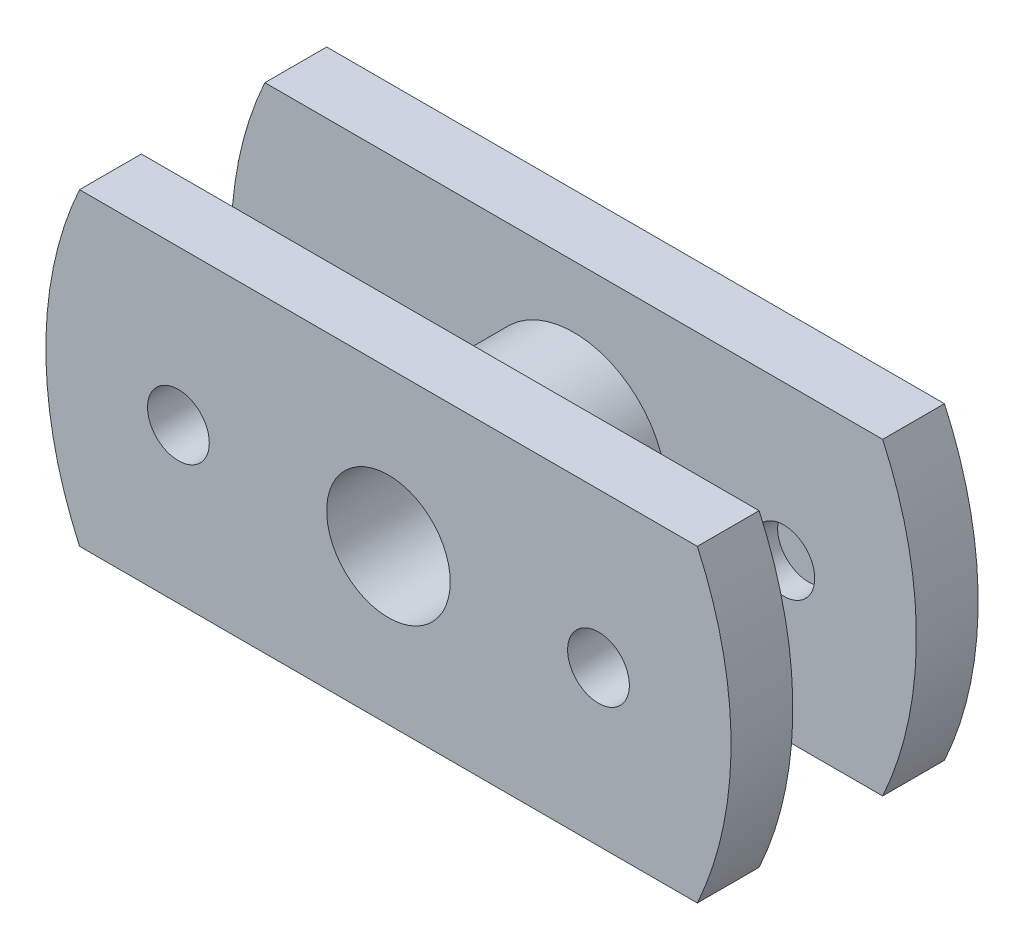
SolidWorks part; units mm, degrees
ref_plane "Front Plane" through (0, 0, 0) normal (0, 0, 1) x (1, 0, 0)
ref_plane "Top Plane" through (0, 0, 0) normal (0, 1, 0) x (1, 0, 0)
ref_plane "Right Plane" through (0, 0, 0) normal (1, 0, 0) x (0, 0, -1)
sketch "Sketch1" plane through (0, 0, 0) normal (0, 0, 1) x (1, 0, 0)
  line L0 (-25, 12.5) -> (-25, -12.5) construction
  line L1 (-25, -12.5) -> (25, -12.5)
  line L3 (-25, 12.5) -> (25, 12.5)
  line L5 (-25, -12.5) -> (25, 12.5) construction
  line L6 (-25, 12.5) -> (25, -12.5) construction
  line L7 (25, 12.5) -> (25, -12.5) construction
  arc A0 (-25, 12.5) -> (-25, -12.5) centre (2.2718, 0) ccw
  arc A1 (25, 12.5) -> (25, -12.5) centre (-2.2718, 0) cw
  point P0 (0, 0)
  dimension "D3" = 30
  dimension "D4" = 30
  dimension "D1" = 50
  dimension "D2" = 25
  dimension "D5" = 50
extrude "Boss-Extrude1" add sketch "Sketch1" along normal blind 5
sketch "Sketch2" plane through (0, 0, 5) normal (0, 0, 1) x (1, 0, 0)
  circle A0 centre (0, 0) radius 7.5
  dimension "D1" = 15
extrude "Boss-Extrude2" add sketch "Sketch2" along normal blind 10
sketch "Sketch3" plane through (0, 0, 5) normal (0, 0, 1) x (1, 0, 0)
  circle A0 centre (17, 0) radius 2.5
  circle A1 centre (-17, 0) radius 2.5
  dimension "D3" = 5
  dimension "D4" = 5
  dimension "D1" = 17
  dimension "D2" = 17
extrude "Cut-Extrude1" cut sketch "Sketch3" against normal blind 2
sketch "Sketch4" plane through (0, 0, 15) normal (0, 0, 1) x (1, 0, 0)
  line L1 (25, 12.5) -> (-25, 12.5)
  line L2 (25, 12.5) -> (25, -12.5) construction
  line L3 (25, -12.5) -> (-25, -12.5)
  line L4 (-25, 12.5) -> (-25, -12.5) construction
  line L5 (25, 12.5) -> (-25, -12.5) construction
  line L6 (25, -12.5) -> (-25, 12.5) construction
  arc A0 (25, -12.5) -> (25, 12.5) centre (-2.2718, 0) ccw
  circle A1 centre (0, 0) radius 7.5
  circle A2 centre (0, 0) radius 7.5
  arc A3 (-25, -12.5) -> (-25, 12.5) centre (2.2718, 0) cw
  dimension "D2" = 30
  dimension "D3" = 30
  dimension "D1" = 0
extrude "Boss-Extrude3" add sketch "Sketch4" along normal blind 5 separate body
sketch "Sketch6" plane through (0, 0, 15) normal (0, 0, 1) x (1, 0, 0)
  circle A0 centre (0, 0) radius 7.5
  dimension "D1" = 15
extrude "Boss-Extrude4" add sketch "Sketch6" along normal blind 5
sketch "Sketch7" plane through (0, 0, 20) normal (0, 0, 1) x (1, 0, 0)
  circle A0 centre (0, 0) radius 5
  dimension "D1" = 10
extrude "Cut-Extrude2" cut sketch "Sketch7" against normal blind 15
sketch "Sketch8" plane through (0, 0, 20) normal (0, 0, 1) x (1, 0, 0)
  line L2 (-25, -12.5) -> (25, -12.5)
  line L3 (25, 12.5) -> (-25, 12.5)
  line L4 (-25, -12.5) -> (25, -12.5)
  line L5 (25, 12.5) -> (-25, 12.5)
  circle A0 centre (17, 0) radius 2.5
  circle A1 centre (-17, 0) radius 2.5
  arc A2 (-25, 12.5) -> (-25, -12.5) centre (2.2718, 0) ccw
  arc A3 (25, -12.5) -> (25, 12.5) centre (-2.2718, 0) ccw
  arc A4 (-25, 12.5) -> (-25, -12.5) centre (2.2718, 0) ccw
  arc A5 (25, -12.5) -> (25, 12.5) centre (-2.2718, 0) ccw
  dimension "D4" = 5
  dimension "D5" = 5
  dimension "D2" = 17
  dimension "D3" = 17
  dimension "D1" = 0
extrude "Cut-Extrude3" cut sketch "Sketch8" against normal up to surface (5 mm away) contours A0 | A1 up to face at (0, 0, 15)
